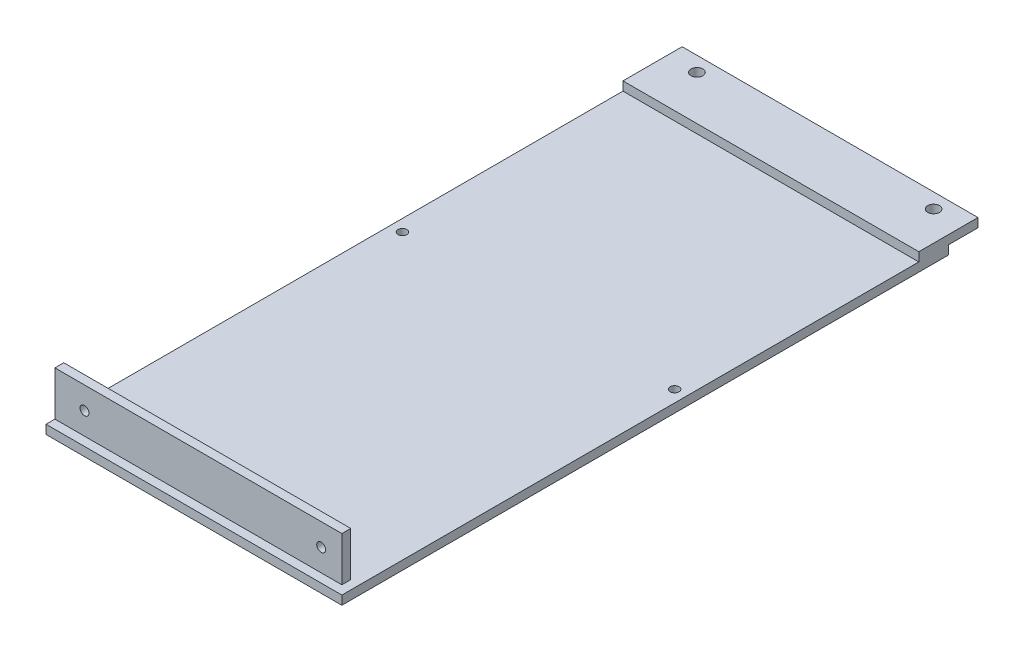
SolidWorks part; units mm, degrees
ref_plane "Front Plane" through (0, 0, 0) normal (0, 0, 1) x (1, 0, 0)
ref_plane "Top Plane" through (0, 0, 0) normal (0, 1, 0) x (1, 0, 0)
ref_plane "Right Plane" through (0, 0, 0) normal (1, 0, 0) x (0, 0, -1)
sketch "Sketch1" plane through (0, 0, 0) normal (0, 1, 0) x (1, 0, 0)
  line L1 (-50, -102.5) -> (50, -102.5)
  line L2 (-50, -102.5) -> (-50, 102.5)
  line L3 (-50, 102.5) -> (50, 102.5)
  line L4 (50, -102.5) -> (50, 102.5)
  line L5 (-50, -102.5) -> (50, 102.5) construction
  line L6 (-50, 102.5) -> (50, -102.5) construction
  point P0 (0, 0)
  dimension "D1" = 205
  dimension "D2" = 100
extrude "Boss-Extrude1" add sketch "Sketch1" along normal blind 3 contours L2 L3 L4 L1
sketch "Sketch2" plane through (0, 3, 0) normal (0, 1, 0) x (1, 0, 0)
  line L0 (-50, -102.5) -> (-50, 102.5) construction
  line L1 (-50, 92.5) -> (50, 92.5)
  line L2 (-50, 92.5) -> (-50, 112.5)
  line L3 (-50, 112.5) -> (50, 112.5)
  line L4 (50, 92.5) -> (50, 112.5)
  line L5 (50, -102.5) -> (50, 102.5) construction
  line L6 (-50, 102.5) -> (50, 102.5) construction
  dimension "D1" = 10
  dimension "D2" = 10
extrude "Boss-Extrude2" add sketch "Sketch2" along normal blind 3
sketch "Sketch3" plane through (0, 6, 0) normal (0, 1, 0) x (1, 0, 0)
  line L0 (50, 112.5) -> (-50, 112.5) construction
  line L1 (-50, 112.5) -> (-50, 92.5) construction
  circle A0 centre (-40, 107.5) radius 2
  dimension "D1" = 4
  dimension "D2" = 5
  dimension "D3" = 10
extrude "Cut-Extrude1" cut sketch "Sketch3" against normal up to next
pattern_linear "LPattern1" count 2 spacing 80 along (1, 0, 0) of "Cut-Extrude1"
sketch "Sketch4" plane through (0, 3, 0) normal (0, 1, 0) x (1, 0, 0)
  line L0 (-50, -102.5) -> (-50, 92.5) construction
  line L1 (-50, -99.5) -> (50, -99.5)
  line L2 (-50, -99.5) -> (-50, -96.5)
  line L3 (-50, -96.5) -> (50, -96.5)
  line L4 (50, -99.5) -> (50, -96.5)
  line L5 (50, -102.5) -> (50, 92.5) construction
  line L6 (-50, -102.5) -> (50, -102.5) construction
  dimension "D1" = 3
  dimension "D2" = 3
extrude "Boss-Extrude3" add sketch "Sketch4" along normal blind 15
sketch "Sketch5" plane through (0, 0, 99.5) normal (0, 0, 1) x (1, 0, 0)
  line L0 (-50, 18) -> (-50, 3) construction
  line L1 (-50, 18) -> (50, 18) construction
  circle A0 centre (-40, 10.5) radius 1.5
  dimension "D1" = 3
  dimension "D2" = 10
  dimension "D3" = 7.5
extrude "Cut-Extrude2" cut sketch "Sketch5" against normal up to next
pattern_linear "LPattern2" count 2 spacing 80 along (1, 0, 0) of "Cut-Extrude2"
sketch "Sketch6" plane through (0, 3, 0) normal (0, 1, 0) x (1, 0, 0)
  line L0 (-50, -96.5) -> (-50, 92.5) construction
  line L1 (50, -96.5) -> (50, 92.5) construction
  circle A0 centre (-46, 13.97) radius 1.5
  circle A1 centre (46, 13.97) radius 1.5
  point P8 (0, 0)
  point P9 (-46, 9.3295)
  point P11 (-46, 10.1954)
  dimension "D1" = 3
  dimension "D2" = 3
  dimension "D3" = 4
  dimension "D4" = 4
  dimension "D5" = 13.97
sketch "Sketch7" plane through (50, 0, 0) normal (1, 0, 0) x (0, 0, -1)
  line L1 (-99.5, 18) -> (-96.5, 18)
  line L2 (-99.5, 18) -> (-99.5, 3)
  line L3 (-99.5, 3) -> (-96.5, 3)
  line L4 (-96.5, 18) -> (-96.5, 3)
extrude "Cut-Extrude3" cut sketch "Sketch7" against normal blind 3
extrude "Cut-Extrude4" cut sketch "Sketch6" against normal up to next
